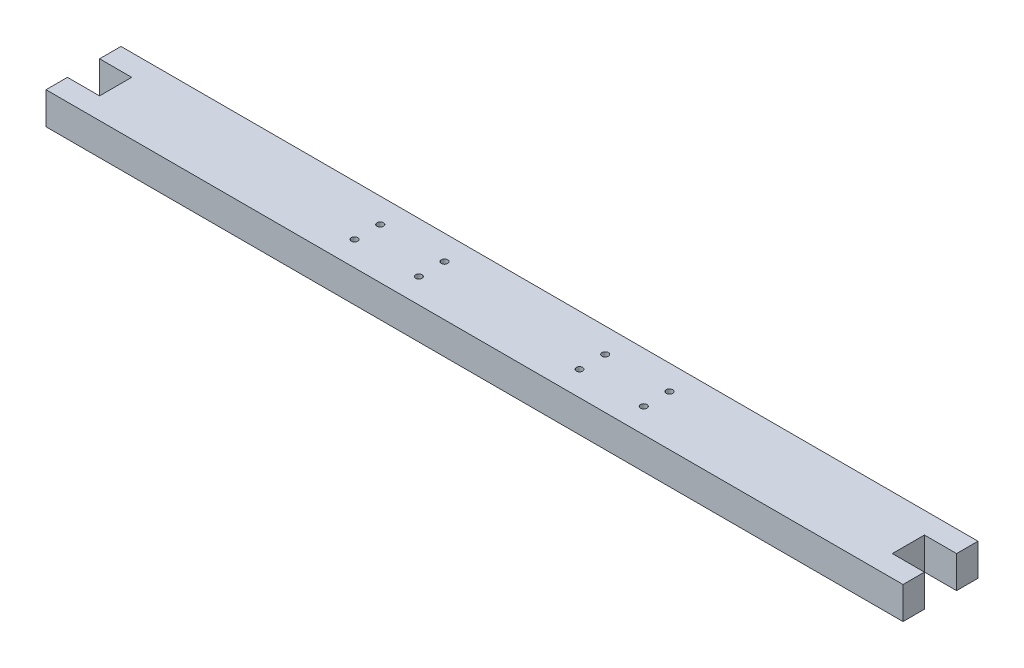
SolidWorks part; units mm, degrees
ref_plane "前视基准面" through (0, 0, 0) normal (0, 0, 1) x (1, 0, 0)
ref_plane "上视基准面" through (0, 0, 0) normal (0, 1, 0) x (1, 0, 0)
ref_plane "右视基准面" through (0, 0, 0) normal (1, 0, 0) x (0, 0, -1)
sketch "草图3" plane through (0, 0, 0) normal (0, 1, 0) x (1, 0, 0)
  line L0 (0, 0) -> (400, 0)
  line L1 (0, 0) -> (0, 10)
  line L2 (400, 0) -> (400, 10)
  line L3 (0, 35) -> (400, 35)
  line L4 (0, 10) -> (15, 10)
  line L6 (15, 10) -> (15, 25)
  line L7 (0, 25) -> (15, 25)
  line L8 (0, 25) -> (0, 35)
  line L10 (400, 10) -> (385, 10)
  line L11 (400, 25) -> (385, 25)
  line L12 (385, 10) -> (385, 25)
  line L13 (400, 25) -> (400, 35)
  dimension "D1" = 10
  dimension "D2" = 10
  dimension "D3" = 10
  dimension "D4" = 15
  dimension "D5" = 10
  dimension "D6" = 15
  dimension "D7" = 400
  dimension "D8" = 15
  dimension "D9" = 15
  dimension "D10" = 15
extrude "凸台-拉伸1" add sketch "草图3" along normal blind 15 contours L3 L13 L11 L12 L10 L2 L0 L1 L4 L6 L7 L8
sketch "草图4" plane through (0, 15, 0) normal (0, 1, 0) x (1, 0, 0)
  line L0 (15, 10) -> (15, 25) construction
  line L1 (237.5, 11.5) -> (162.5, 11.5) construction
  line L2 (237.5, 11.5) -> (237.5, 23.5) construction
  line L3 (237.5, 23.5) -> (162.5, 23.5) construction
  line L4 (162.5, 11.5) -> (162.5, 23.5) construction
  line L5 (237.5, 11.5) -> (162.5, 23.5) construction
  line L6 (237.5, 23.5) -> (162.5, 11.5) construction
  line L7 (237.5, 23.5) -> (267.5, 23.5) construction
  line L8 (237.5, 23.5) -> (237.5, 11.5) construction
  line L9 (237.5, 11.5) -> (267.5, 11.5) construction
  line L10 (267.5, 23.5) -> (267.5, 11.5) construction
  line L11 (162.5, 23.5) -> (132.5, 23.5) construction
  line L12 (162.5, 23.5) -> (162.5, 11.5) construction
  line L13 (162.5, 11.5) -> (132.5, 11.5) construction
  line L14 (132.5, 23.5) -> (132.5, 11.5) construction
  circle A0 centre (267.5, 11.5) radius 1.5
  circle A1 centre (267.5, 23.5) radius 1.5
  circle A2 centre (237.5, 11.5) radius 1.5
  circle A3 centre (237.5, 23.5) radius 1.5
  circle A4 centre (162.5, 11.5) radius 1.5
  circle A5 centre (132.5, 11.5) radius 1.5
  circle A6 centre (132.5, 23.5) radius 1.5
  circle A7 centre (162.5, 23.5) radius 1.5
  point P0 (200, 17.5)
  dimension "D3" = 30
  dimension "D1" = 75
  dimension "D2" = 12
  dimension "D4" = 30
  dimension "D5" = 185
extrude "切除-拉伸1" cut sketch "草图4" against normal blind 15
